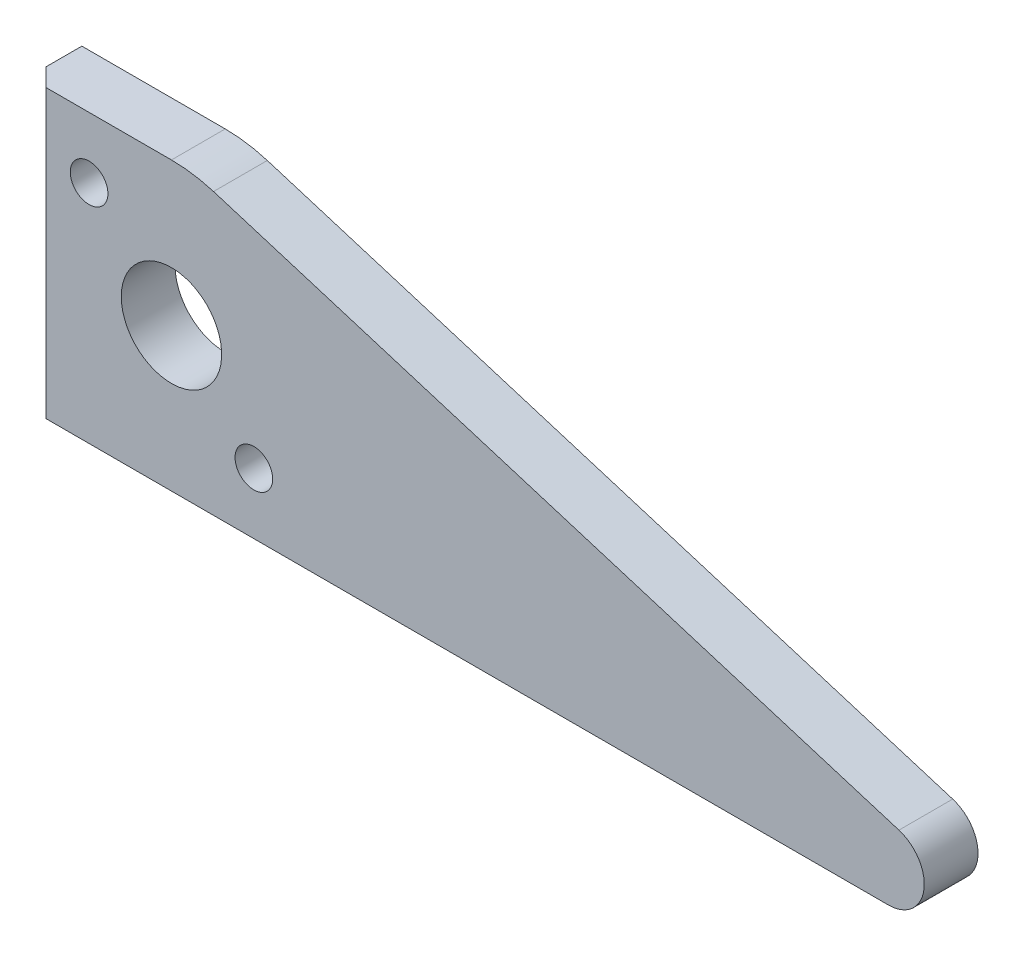
SolidWorks part; units mm, degrees
material "3.3549 (EN-AW 5182)"
ref_plane "Piano frontale" through (0, 0, 0) normal (0, 0, 1) x (1, 0, 0)
ref_plane "Piano superiore" through (0, 0, 0) normal (0, 1, 0) x (1, 0, 0)
ref_plane "Piano destro" through (0, 0, 0) normal (1, 0, 0) x (0, 0, -1)
sketch "Schizzo1" plane through (0, 0, 0) normal (0, 0, 1) x (1, 0, 0)
  line L1 (-40, 40) -> (0, 40)
  line L2 (-40, 40) -> (-40, -40)
  line L3 (-40, -40) -> (0, -40)
  arc A0 (0, -40) -> (0, 40) centre (0, 0) ccw
  dimension "D1" = 80
  dimension "D2" = 40
extrude "Estrusione1" add sketch "Schizzo1" along normal blind 15
chamfer "Smusso1" distance 5 angle 45 1 edges at (-40, 0, 15)
sketch "Schizzo2" plane through (0, 0, 0) normal (0, 0, -1) x (-1, 0, 0)
  circle A0 centre (0, 0) radius 14
  dimension "D1" = 28
extrude "Taglio-Estrusione1" cut sketch "Schizzo2" against normal through all
sketch "Schizzo4" plane through (0, 0, 15) normal (0, 0, 1) x (1, 0, 0)
  line L0 (-37.8193, 37.8193) -> (45.5753, -45.5753) construction
  line L1 (-111.1672, 0) -> (84.1309, 0) construction
  circle A0 centre (0, 0) radius 32.5 construction
  circle A1 centre (-22.981, 22.981) radius 3
  circle A2 centre (22.981, -22.981) radius 3
  dimension "D1" = 65
  dimension "D2" = 6
  dimension "D3" = 45
  dimension "D4" = 6
extrude "Taglio-Estrusione3" cut sketch "Schizzo4" against normal blind 20
sketch "Schizzo5" plane through (0, 0, 15) normal (0, 0, 1) x (1, 0, 0)
  line L0 (-108.9757, 0) -> (49.4015, 0) construction
  circle A1 centre (-22.981, 22.981) radius 5.25
  circle A2 centre (22.981, -22.981) radius 5.25
  dimension "D1" = 10.5
  dimension "D2" = 10.5
extrude "Taglio-Estrusione4" cut sketch "Schizzo5" against normal blind 8.5
sketch "Schizzo6" plane through (0, 0, 15) normal (0, 0, 1) x (1, 0, 0)
  line L0 (11.7359, 38.2396) -> (202.934, -20.4401)
  line L1 (0, -40) -> (200, -40)
  arc A0 (0, -40) -> (0, 40) centre (0, 0) ccw construction
  arc A1 (0, -40) -> (11.7359, 38.2396) centre (0, 0) ccw
  arc A2 (200, -40) -> (202.934, -20.4401) centre (200, -30) ccw
  dimension "D2" = 10
  dimension "D1" = 200
extrude "Estrusione2" add sketch "Schizzo6" against normal up to surface (15 mm away) up to face at (25.981, -22.981, 0)
sketch "Schizzo7" plane through (0, 0, 15) normal (0, 0, 1) x (1, 0, 0)
  line L0 (-35.1989, 0) -> (34.6391, 0) construction
  line L1 (0, 34.1374) -> (0, -36.9742) construction
  circle A4 centre (27.5, 0) radius 2.5
  circle A5 centre (0, -27.5) radius 2.5
  circle A6 centre (-27.5, 0) radius 2.5
  circle A7 centre (0, 27.5) radius 2.5
  circle A8 centre (0, 0) radius 27.5 construction
  dimension "D1" = 55
  dimension "D2" = 5
  dimension "D3" = 5
  dimension "D4" = 5
  dimension "D5" = 5
extrude "Taglio-Estrusione5" [suppressed] cut sketch "Schizzo7" against normal through all
sketch "Schizzo8" [suppressed] plane through (0, 0, 0) normal (0, 0, -1) x (-1, 0, 0)
  circle A1 centre (0, 27.5) radius 4.25
  circle A2 centre (-27.5, 0) radius 4.25
  circle A3 centre (0, -27.5) radius 4.25
  circle A4 centre (27.5, 0) radius 4.25
  dimension "D1" = 8.5
  dimension "D2" = 8.5
  dimension "D3" = 8.5
  dimension "D4" = 8.5
extrude "Taglio-Estrusione6" [suppressed] cut sketch "Schizzo8" against normal blind 6
sketch "Schizzo9" plane through (0, 0, 0) normal (0, 0, -1) x (-1, 0, 0)
  line L1 (-57, -57.0354) -> (-57, 23.5027) construction
  line L2 (-227.5299, -33.5) -> (-35.6173, -33.5) construction
  line L4 (40, -40) -> (-200, -40) construction
  line L5 (-57, -8.6484) -> (-138.2859, -33.5) construction
  circle A0 centre (-57, -8.6484) radius 3
  circle A1 centre (-138.2859, -33.5) radius 3
  dimension "D5" = 6
  dimension "D6" = 6
  dimension "D1" = 17
  dimension "D2" = 57
  dimension "D3" = 85
  dimension "D4" = 6.5
extrude "Taglio-Estrusione7" cut sketch "Schizzo9" against normal blind 10
